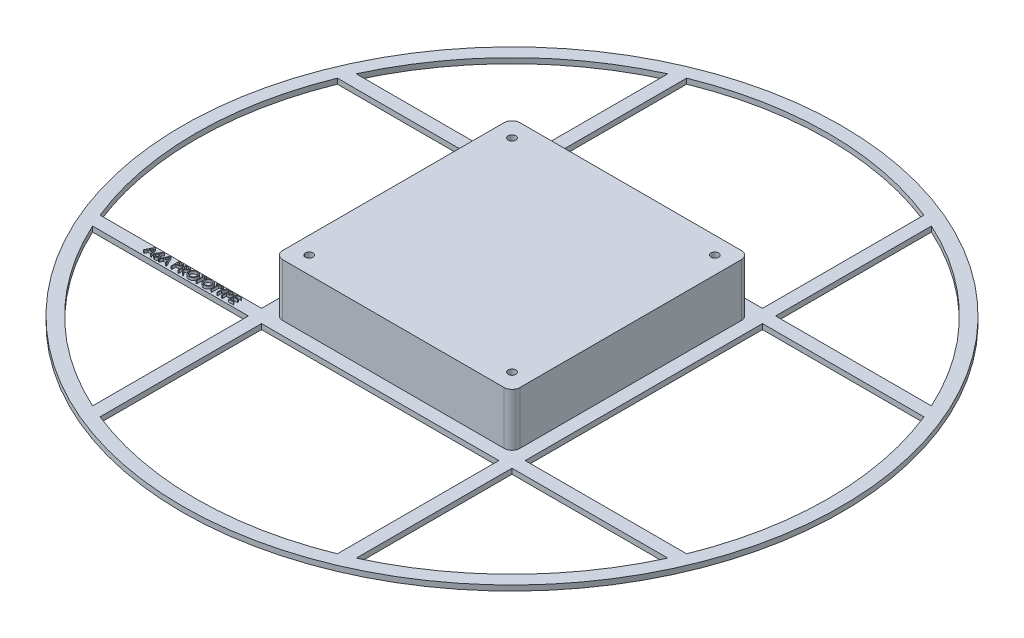
SolidWorks part; units mm, degrees
ref_plane "Front Plane" through (0, 0, 0) normal (0, 0, 1) x (1, 0, 0)
ref_plane "Top Plane" through (0, 0, 0) normal (0, 1, 0) x (1, 0, 0)
ref_plane "Right Plane" through (0, 0, 0) normal (1, 0, 0) x (0, 0, -1)
sketch "Sketch1" plane through (0, 0, 0) normal (0, 1, 0) x (1, 0, 0)
  line L0 (-125, 0) -> (125, 0) construction
  line L1 (0, -125) -> (0, 125) construction
  line L11 (-50, -50) -> (50, -50)
  line L12 (-50, -50) -> (-50, 50)
  line L13 (-50, 50) -> (50, 50)
  line L14 (50, -50) -> (50, 50)
  line L15 (-50, -50) -> (50, 50) construction
  line L16 (-50, 50) -> (50, -50) construction
  circle A0 centre (0, 0) radius 125
  circle A1 centre (0, 0) radius 120
  dimension "D1" = 250
  dimension "D3" = 100
  dimension "D2" = 5
extrude "Boss-Extrude1" add sketch "Sketch1" along normal blind 2 contours A0 A1 | L11 L14 L13 L12
sketch "Sketch2" plane through (-50, 0, 0) normal (-1, 0, 0) x (0, 0, 1)
  line L0 (50, 0) -> (-50, 0) construction
  line L1 (-50, 2) -> (-45, 2)
  line L2 (-50, 2) -> (-50, 0)
  line L3 (-50, 0) -> (-45, 0)
  line L4 (-45, 2) -> (-45, 0)
  dimension "D1" = 5
extrude "Boss-Extrude2" add sketch "Sketch2" along normal up to next
mirror "Mirror1" about plane through (0, 0, 0) normal (1, 0, 0) of "Boss-Extrude2" second plane through (0, 0, 0) second plane normal (0, 0, 1)
sketch "Sketch5" plane through (0, 2, 0) normal (0, 1, 0) x (1, 0, 0)
  line L0 (-50, 45) -> (-50, 50) construction
  line L1 (-109.0871, 50) -> (109.0871, 50) construction
  line L2 (-50, 50) -> (50, -50) construction
  line L3 (-109.0871, -50) -> (109.0871, -50) construction
  line L4 (50, 45) -> (50, 50) construction
  line L5 (50, 50) -> (-50, -50) construction
ref_plane "Plane1" through (0, 0, 0) normal (-0.7071, 0, 0.7071) x (0.7071, 0, 0.7071)
ref_plane "Plane2" through (0, 0, 0) normal (-0.7071, 0, -0.7071) x (-0.7071, 0, 0.7071)
mirror "Mirror2" about plane through (0, 0, 0) normal (-0.7071, 0, -0.7071) of "Boss-Extrude2" second plane through (0, 0, 0) second plane normal (-0.7071, 0, 0.7071)
mirror "Mirror3" about plane through (0, 0, 0) normal (1, 0, 0) of "Mirror2"
sketch "Sketch8" plane through (0, 2, 0) normal (0, 1, 0) x (1, 0, 0)
  line L0 (-50, 50) -> (50, -50) construction
  line L1 (-45, 45) -> (45, 45)
  line L2 (-45, 45) -> (-45, -45)
  line L3 (-45, -45) -> (45, -45)
  line L4 (45, 45) -> (45, -45)
extrude "Boss-Extrude3" add sketch "Sketch8" along normal blind 20
fillet "Fillet1" radius 3 4 edges at (-45, 12, -45) (45, 12, -45) (45, 12, 45) (-45, 12, 45)
sketch "Sketch9" plane through (0, 22, 0) normal (0, 1, 0) x (1, 0, 0)
  line L0 (-50, 50) -> (50, -50) construction
  circle A0 centre (-38.4645, 38.4645) radius 1.45
  arc A1 (-42, 45) -> (-45, 42) centre (-42, 42) ccw construction
  circle A2 centre (38.4645, 38.4645) radius 1.45
  circle A3 centre (38.4645, -38.4645) radius 1.45
  circle A4 centre (-38.4645, -38.4645) radius 1.45
  point P16 (0, 0)
  dimension "D1" = 2.9
  dimension "D2" = 5
  dimension "D3" = 4
extrude "Cut-Extrude1" cut sketch "Sketch9" against normal blind 15
sketch "Sketch11" plane through (0, 2, 0) normal (0, 1, 0) x (1, 0, 0)
  text T0 "A6A PROTOTYPE"
extrude "Boss-Extrude4" add sketch "Sketch11" along normal blind 1
